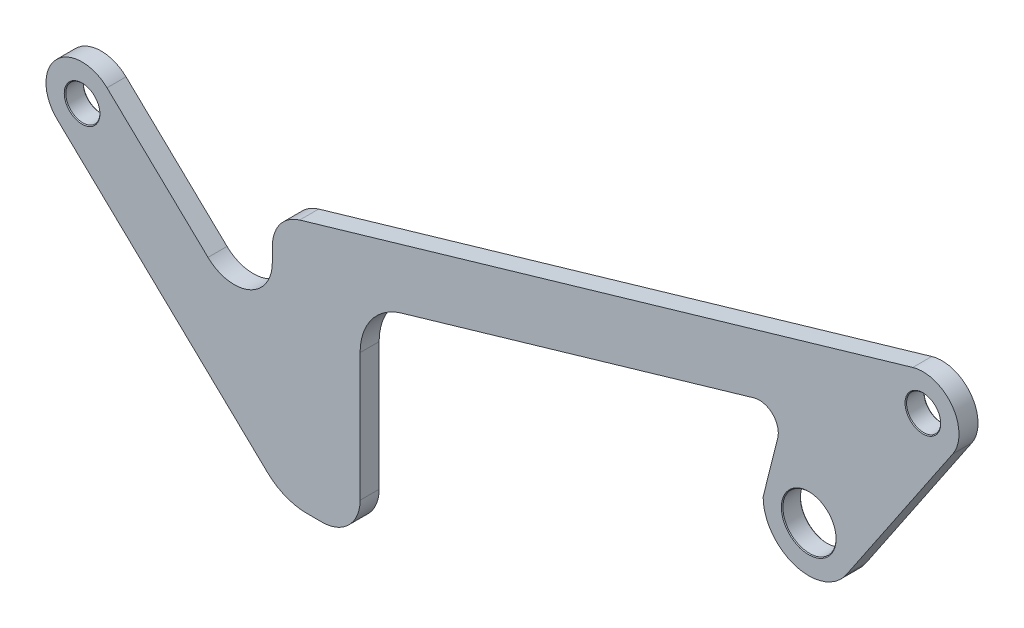
SolidWorks part; units mm, degrees
ref_plane "Front Plane" through (0, 0, 0) normal (0, 0, 1) x (1, 0, 0)
ref_plane "Top Plane" through (0, 0, 0) normal (0, 1, 0) x (1, 0, 0)
ref_plane "Right Plane" through (0, 0, 0) normal (1, 0, 0) x (0, 0, -1)
sketch "Sketch1" plane through (0, 0, 0) normal (0, 0, 1) x (1, 0, 0)
  line L11 (-191, 0) -> (1.1294, 0) construction
  line L13 (-133.8005, 2.1003) -> (27.3423, 49.1102)
  line L14 (-197.5506, -6.8666) -> (-142.2704, -59.6026)
  line L15 (-184.4494, 6.8666) -> (-157.9026, -18.4585)
  line L16 (-141, -7.4996) -> (-141, -11.2229)
  line L17 (37.8672, 34.6927) -> (9.9397, -6.7054)
  line L19 (-117.9237, -20.1426) -> (-117.9237, -53.7492)
  line L20 (-127.9237, -63.7492) -> (-131.9165, -63.7492)
  line L21 (-107.1246, -5.7428) -> (-14.398, 21.3082)
  line L22 (-8.1484, 15.2899) -> (-11.99, 0)
  circle A0 centre (0, 0) radius 6.99
  circle A1 centre (-191, 0) radius 4.49
  circle A2 centre (30, 40) radius 4.49
  arc A15 (-184.4494, 6.8666) -> (-197.5506, -6.8666) centre (-191, 0) ccw
  arc A16 (-11.99, 0) -> (9.9397, -6.7054) centre (0, 0) ccw
  arc A17 (37.8672, 34.6927) -> (27.3423, 49.1102) centre (30, 40) ccw
  arc A18 (-141, -11.2229) -> (-157.9026, -18.4585) centre (-151, -11.2229) cw
  arc A19 (-131.9165, -63.7492) -> (-142.2704, -59.6026) centre (-131.9165, -48.7492) cw
  arc A20 (-127.9237, -63.7492) -> (-117.9237, -53.7492) centre (-127.9237, -53.7492) ccw
  arc A21 (-133.8005, 2.1003) -> (-141, -7.4996) centre (-131, -7.4996) ccw
  arc A23 (-8.1484, 15.2899) -> (-14.398, 21.3082) centre (-12.9977, 16.5082) ccw
  arc A24 (-117.9237, -20.1426) -> (-107.1246, -5.7428) centre (-102.9237, -20.1426) cw
  point P17 (39.49, 120)
  point P26 (-137.9237, -63.7492)
  point P29 (-117.9237, -63.7492)
  point P32 (-141, 0)
  dimension "D1" = 8.98
  dimension "D2" = 13.98
  dimension "D3" = 8.98
  dimension "D6" = 5
  dimension "D7" = 5
  dimension "D8" = 5
  dimension "D10" = 20
  dimension "D11" = 50
  dimension "D12" = 10
  dimension "D13" = 15
  dimension "D14" = 10
  dimension "D15" = 10
  dimension "D16" = 15
  dimension "D17" = 5
  dimension "D18" = 15
  dimension "D4" = 191
  dimension "D5" = 40
  dimension "D9" = 50
extrude "Boss-Extrude1" add sketch "Sketch1" along normal blind 5
ref_plane "Plane1" through (0, 0, -0.5) normal (0, 0, 1) x (1, 0, 0)
sketch "Sketch2" plane through (0, 0, 5) normal (0, 0, 1) x (1, 0, 0)
  line L0 (-191, 0) -> (0, 0) construction
chamfer "Chamfer1" distance 0.2 angle 45 2 edges at (-186.51, 0, 0) (-186.51, 0, 5)
chamfer "Chamfer2" distance 0.2 angle 45 2 edges at (6.99, 0, 0) (6.99, 0, 5)
chamfer "Chamfer3" distance 0.2 angle 45 2 edges at (34.49, 40, 0) (34.49, 40, 5)
